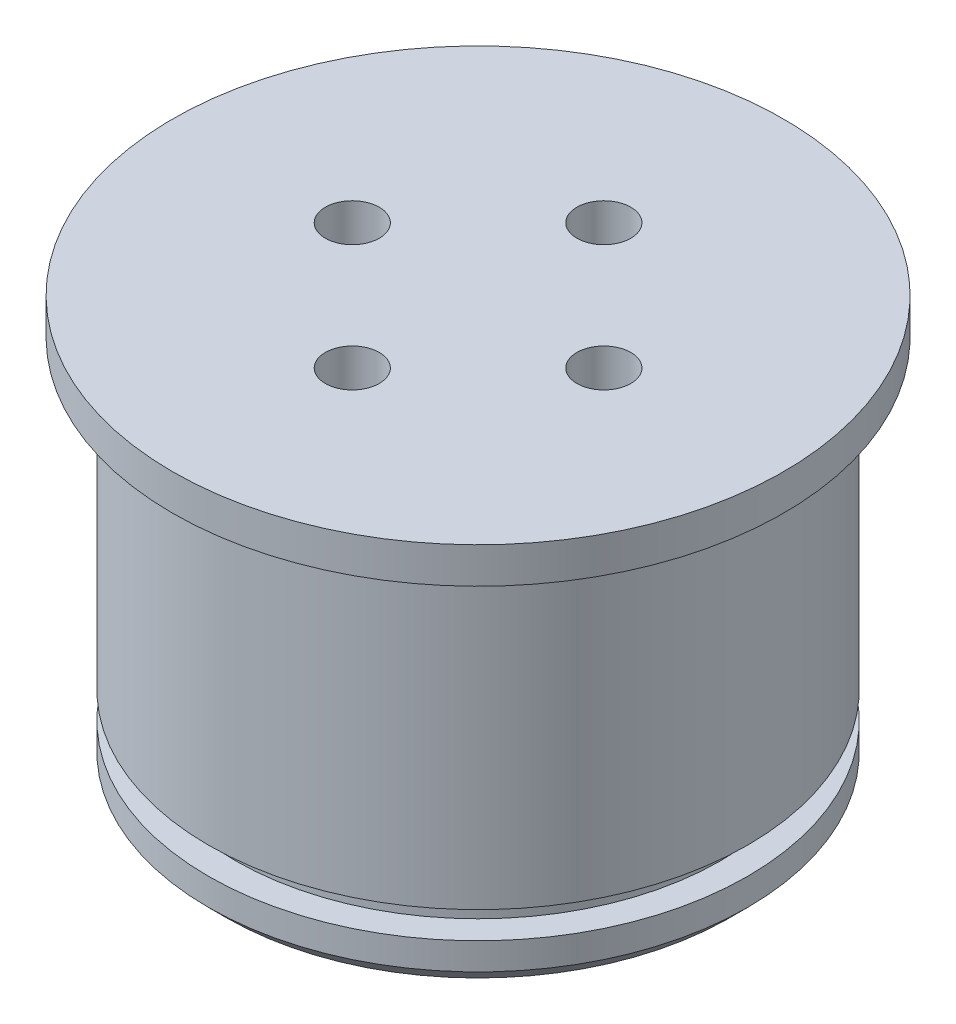
SolidWorks part; units mm, degrees
ref_plane "Спереди" through (0, 0, 0) normal (0, 0, 1) x (1, 0, 0)
ref_plane "Сверху" through (0, 0, 0) normal (0, 1, 0) x (1, 0, 0)
ref_plane "Справа" through (0, 0, 0) normal (1, 0, 0) x (0, 0, -1)
sketch "Эскиз1" plane through (0, 0, 0) normal (0, 1, 0) x (1, 0, 0)
  circle A0 centre (0, 0) radius 15
  dimension "D1" = 30
extrude "Бобышка-Вытянуть1" add sketch "Эскиз1" along normal blind 21
sketch "Эскиз2" plane through (0, 0, 0) normal (0, -1, 0) x (1, 0, 0)
  circle A0 centre (0, 0) radius 10
  dimension "D1" = 20
extrude "Вырез-Вытянуть2" cut sketch "Эскиз2" against normal blind 2.5
ref_plane "Плоскость1" through (0, 2.5, 0) normal (0, -1, 0) x (-1, 0, 0)
sketch "Эскиз5" plane through (0, 2.5, 0) normal (0, -1, 0) x (-1, 0, 0)
  circle A0 centre (0, 0) radius 13.5
  circle A1 centre (0, 0) radius 15
  dimension "D1" = 27
  dimension "D2" = 30
extrude "Вырез-Вытянуть5" cut sketch "Эскиз5" against normal blind 1.5
chamfer "Фаска1" distance 1 angle 45 1 edges at (0, 0, 15)
sketch "Эскиз6" plane through (0, 21, 0) normal (0, 1, 0) x (1, 0, 0)
  circle A0 centre (0, 0) radius 17
  dimension "D1" = 34
extrude "Бобышка-Вытянуть2" add sketch "Эскиз6" along normal blind 2
sketch "Эскиз4" plane through (0, 2.5, 0) normal (0, -1, 0) x (1, 0, 0)
  circle A0 centre (0, 7) radius 1.5
  dimension "D2" = 3
  dimension "D1" = 7
extrude "Вырез-Вытянуть6" cut sketch "Эскиз4" against normal through all
pattern_circular "Круговой массив1" count 4 over 360 about axis through (0, 0, 0) along (0, 1, 0) of "Вырез-Вытянуть6"
